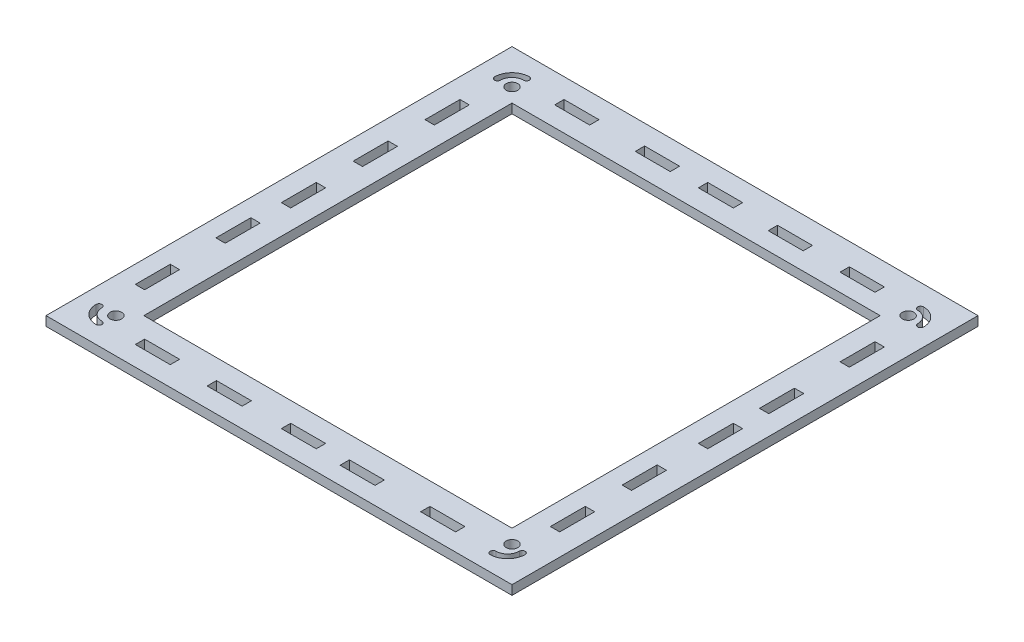
SolidWorks part; units mm, degrees
ref_plane "Alzado" through (0, 0, 0) normal (0, 0, 1) x (1, 0, 0)
ref_plane "Planta" through (0, 0, 0) normal (0, 1, 0) x (1, 0, 0)
ref_plane "Vista lateral" through (0, 0, 0) normal (1, 0, 0) x (0, 0, -1)
sketch "Croquis1" plane through (0, 0, 0) normal (0, 1, 0) x (1, 0, 0)
  line L0 (100, 15) -> (100, 0) construction
  line L1 (0, 0) -> (200, 0)
  line L2 (0, 0) -> (0, 200)
  line L3 (0, 200) -> (200, 200)
  line L4 (200, 0) -> (200, 200)
  line L5 (15, 15) -> (185, 15) construction
  line L6 (15, 15) -> (15, 185) construction
  line L7 (15, 185) -> (185, 185) construction
  line L8 (185, 15) -> (185, 185) construction
  line L9 (185, 100) -> (200, 100) construction
  circle A0 centre (15, 185) radius 2.5
  circle A1 centre (185, 185) radius 2.5
  circle A2 centre (185, 15) radius 2.5
  circle A3 centre (15, 15) radius 2.5
  dimension "D3" = 5
  dimension "D1" = 200
  dimension "D2" = 170
extrude "Saliente-Extruir1" add sketch "Croquis1" along normal blind 4
sketch "Croquis2" plane through (0, 4, 0) normal (0, 1, 0) x (1, 0, 0)
  line L0 (0, 200) -> (200, 0) construction
  line L2 (21, 21) -> (179, 21)
  line L3 (21, 21) -> (21, 179)
  line L4 (21, 179) -> (179, 179)
  line L5 (179, 21) -> (179, 179)
  line L6 (21, 21) -> (179, 179) construction
  line L7 (21, 179) -> (179, 21) construction
  point P4 (100, 100)
  dimension "D1" = 158
extrude "Cortar-Extruir1" cut sketch "Croquis2" against normal blind 10
sketch "Croquis4" plane through (0, 4, 0) normal (0, 1, 0) x (1, 0, 0)
  line L0 (21, 100) -> (0, 100) construction
  line L1 (21, 179) -> (21, 21) construction
  line L2 (0, 200) -> (0, 0) construction
  line L3 (10.5, 100) -> (10.5, 123.3333) construction
  line L4 (8.5, 123.3333) -> (12.5, 123.3333)
  line L5 (8.5, 123.3333) -> (8.5, 138.3333)
  line L6 (8.5, 138.3333) -> (12.5, 138.3333)
  line L7 (12.5, 123.3333) -> (12.5, 138.3333)
  line L8 (8.5, 154.1667) -> (12.5, 154.1667)
  line L9 (8.5, 154.1667) -> (8.5, 169.1667)
  line L10 (8.5, 169.1667) -> (12.5, 169.1667)
  line L11 (12.5, 154.1667) -> (12.5, 169.1667)
  line L12 (10.5, 123.3333) -> (10.5, 138.3333) construction
  line L13 (10.5, 138.3333) -> (10.5, 154.1667) construction
  line L14 (10.5, 154.1667) -> (10.5, 169.1667) construction
  line L15 (10.5, 169.1667) -> (10.5, 200) construction
  line L16 (200, 200) -> (0, 200) construction
  line L17 (100, 179) -> (100, 200) construction
  line L18 (179, 179) -> (21, 179) construction
  line L19 (100, 189.5) -> (80.4167, 189.5) construction
  line L20 (30.8333, 191.5) -> (45.8333, 191.5)
  line L21 (30.8333, 191.5) -> (30.8333, 187.5)
  line L22 (30.8333, 187.5) -> (45.8333, 187.5)
  line L23 (45.8333, 191.5) -> (45.8333, 187.5)
  line L24 (65.4167, 191.5) -> (80.4167, 191.5)
  line L25 (65.4167, 191.5) -> (65.4167, 187.5)
  line L26 (65.4167, 187.5) -> (80.4167, 187.5)
  line L27 (80.4167, 191.5) -> (80.4167, 187.5)
  line L28 (80.4167, 189.5) -> (65.4167, 189.5) construction
  line L29 (65.4167, 189.5) -> (45.8333, 189.5) construction
  line L30 (45.8333, 189.5) -> (30.8333, 189.5) construction
  line L31 (30.8333, 189.5) -> (0, 189.5) construction
  line L32 (10, 185) -> (7.5, 185) construction
  line L33 (15, 190) -> (15, 192.5) construction
  line L34 (21, 179) -> (179, 21) construction
  line L35 (191.5646, 133.6466) -> (187.5646, 133.6466)
  line L36 (191.5646, 133.6466) -> (191.5646, 118.6466)
  line L37 (191.5646, 118.6466) -> (187.5646, 118.6466)
  line L38 (187.5646, 133.6466) -> (187.5646, 118.6466)
  line L39 (191.5646, 168.2299) -> (187.5646, 168.2299)
  line L40 (191.5646, 168.2299) -> (191.5646, 153.2299)
  line L41 (191.5646, 153.2299) -> (187.5646, 153.2299)
  line L42 (187.5646, 168.2299) -> (187.5646, 153.2299)
  line L43 (123.3979, 190.5633) -> (138.3979, 190.5633)
  line L44 (123.3979, 190.5633) -> (123.3979, 186.5633)
  line L45 (123.3979, 186.5633) -> (138.3979, 186.5633)
  line L46 (138.3979, 190.5633) -> (138.3979, 186.5633)
  line L47 (154.2313, 190.5633) -> (169.2313, 190.5633)
  line L48 (154.2313, 190.5633) -> (154.2313, 186.5633)
  line L49 (154.2313, 186.5633) -> (169.2313, 186.5633)
  line L50 (169.2313, 190.5633) -> (169.2313, 186.5633)
  line L51 (133.7112, 7.4987) -> (133.7112, 11.4987)
  line L52 (133.7112, 7.4987) -> (118.7112, 7.4987)
  line L53 (118.7112, 7.4987) -> (118.7112, 11.4987)
  line L54 (133.7112, 11.4987) -> (118.7112, 11.4987)
  line L55 (168.2945, 7.4987) -> (168.2945, 11.4987)
  line L56 (168.2945, 7.4987) -> (153.2945, 7.4987)
  line L57 (153.2945, 7.4987) -> (153.2945, 11.4987)
  line L58 (168.2945, 11.4987) -> (153.2945, 11.4987)
  line L59 (190.6279, 75.6653) -> (190.6279, 60.6653)
  line L60 (190.6279, 75.6653) -> (186.6279, 75.6653)
  line L61 (186.6279, 75.6653) -> (186.6279, 60.6653)
  line L62 (190.6279, 60.6653) -> (186.6279, 60.6653)
  line L63 (190.6279, 44.832) -> (190.6279, 29.832)
  line L64 (190.6279, 44.832) -> (186.6279, 44.832)
  line L65 (186.6279, 44.832) -> (186.6279, 29.832)
  line L66 (190.6279, 29.832) -> (186.6279, 29.832)
  line L67 (7.5633, 65.3521) -> (11.5633, 65.3521)
  line L68 (7.5633, 65.3521) -> (7.5633, 80.3521)
  line L69 (7.5633, 80.3521) -> (11.5633, 80.3521)
  line L70 (11.5633, 65.3521) -> (11.5633, 80.3521)
  line L71 (7.5633, 30.7687) -> (11.5633, 30.7687)
  line L72 (7.5633, 30.7687) -> (7.5633, 45.7687)
  line L73 (7.5633, 45.7687) -> (11.5633, 45.7687)
  line L74 (11.5633, 30.7687) -> (11.5633, 45.7687)
  line L75 (75.7299, 8.4354) -> (60.7299, 8.4354)
  line L76 (75.7299, 8.4354) -> (75.7299, 12.4354)
  line L77 (75.7299, 12.4354) -> (60.7299, 12.4354)
  line L78 (60.7299, 8.4354) -> (60.7299, 12.4354)
  line L79 (44.8966, 8.4354) -> (29.8966, 8.4354)
  line L80 (44.8966, 8.4354) -> (44.8966, 12.4354)
  line L81 (44.8966, 12.4354) -> (29.8966, 12.4354)
  line L82 (29.8966, 8.4354) -> (29.8966, 12.4354)
  line L83 (107.5, 191.5) -> (92.5, 191.5)
  line L84 (8.5, 107.5) -> (12.5, 107.5)
  line L85 (8.5, 107.5) -> (8.5, 92.5)
  line L86 (8.5, 92.5) -> (12.5, 92.5)
  line L87 (12.5, 107.5) -> (12.5, 92.5)
  line L88 (8.5, 107.5) -> (12.5, 92.5) construction
  line L89 (8.5, 92.5) -> (12.5, 107.5) construction
  line L90 (107.5, 191.5) -> (107.5, 187.5)
  line L91 (107.5, 187.5) -> (92.5, 187.5)
  line L92 (92.5, 191.5) -> (92.5, 187.5)
  line L93 (191.5, 92.5) -> (191.5, 107.5)
  line L94 (191.5, 92.5) -> (187.5, 92.5)
  line L95 (187.5, 92.5) -> (187.5, 107.5)
  line L96 (191.5, 107.5) -> (187.5, 107.5)
  line L97 (92.5, 8.5) -> (107.5, 8.5)
  line L98 (92.5, 8.5) -> (92.5, 12.5)
  line L99 (92.5, 12.5) -> (107.5, 12.5)
  line L100 (107.5, 8.5) -> (107.5, 12.5)
  line L101 (0, 179) -> (21, 179) construction
  line L102 (21, 179) -> (21, 200) construction
  line L103 (15, 185) -> (0, 185) construction
  line L104 (12.5, 138.3333) -> (12.5, 154.1667) construction
  line L105 (12.5, 107.5) -> (12.5, 123.3333) construction
  line L106 (12.5, 169.1667) -> (12.5, 185) construction
  arc A0 (15, 192.5) -> (7.5, 185) centre (15, 185) ccw
  arc A1 (15, 190) -> (10, 185) centre (15, 185) ccw
  arc A2 (7.5, 185) -> (10, 185) centre (8.75, 185) ccw
  arc A3 (15, 190) -> (15, 192.5) centre (15, 191.25) ccw
  arc A4 (185.0646, 191.5633) -> (185.0646, 189.0633) centre (185.0646, 190.3133) ccw
  arc A5 (190.0646, 184.0633) -> (185.0646, 189.0633) centre (185.0646, 184.0633) ccw
  arc A6 (190.0646, 184.0633) -> (192.5646, 184.0633) centre (191.3146, 184.0633) ccw
  arc A7 (192.5646, 184.0633) -> (185.0646, 191.5633) centre (185.0646, 184.0633) ccw
  arc A8 (191.6279, 13.9987) -> (189.1279, 13.9987) centre (190.3779, 13.9987) ccw
  arc A9 (184.1279, 8.9987) -> (189.1279, 13.9987) centre (184.1279, 13.9987) ccw
  arc A10 (184.1279, 8.9987) -> (184.1279, 6.4987) centre (184.1279, 7.7487) ccw
  arc A11 (184.1279, 6.4987) -> (191.6279, 13.9987) centre (184.1279, 13.9987) ccw
  arc A12 (14.0633, 7.4354) -> (14.0633, 9.9354) centre (14.0633, 8.6854) ccw
  arc A13 (9.0633, 14.9354) -> (14.0633, 9.9354) centre (14.0633, 14.9354) ccw
  arc A14 (9.0633, 14.9354) -> (6.5633, 14.9354) centre (7.8133, 14.9354) ccw
  arc A15 (6.5633, 14.9354) -> (14.0633, 7.4354) centre (14.0633, 14.9354) ccw
  point P127 (12.5, 164.4418)
  point P142 (0, 0)
  point P143 (12.5, 170.4415)
  dimension "D4" = 10
  dimension "D5" = 2.5
  dimension "D1" = 15
  dimension "D2" = 4
  dimension "D6" = 4
  dimension "D7" = 4
extrude "Cortar-Extruir2" cut sketch "Croquis4" against normal blind 10
